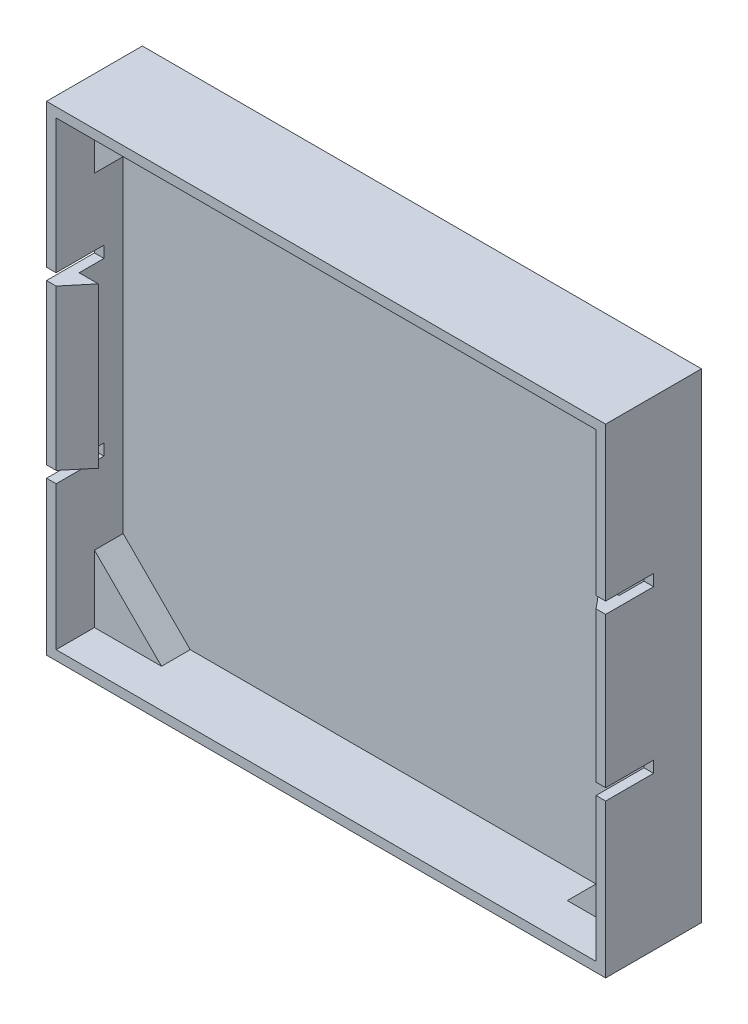
SolidWorks part; units mm, degrees
ref_plane "前基準面" through (0, 0, 0) normal (0, 0, 1) x (1, 0, 0)
ref_plane "上基準面" through (0, 0, 0) normal (0, 1, 0) x (1, 0, 0)
ref_plane "右基準面" through (0, 0, 0) normal (1, 0, 0) x (0, 0, -1)
sketch "草圖1" plane through (0, 0, 0) normal (0, 0, 1) x (1, 0, 0)
  line L1 (-24.8424, 31.8654) -> (33.5176, 31.8654)
  line L2 (-24.8424, 31.8654) -> (-24.8424, -18.2046)
  line L3 (-24.8424, -18.2046) -> (33.5176, -18.2046)
  line L4 (33.5176, 31.8654) -> (33.5176, -18.2046)
  dimension "D1" = 58.36
  dimension "D2" = 50.07
extrude "填料-伸長1" add sketch "草圖1" along normal blind 3
sketch "草圖2" plane through (0, 0, 3) normal (0, 0, 1) x (1, 0, 0)
  line L1 (-24.8424, 31.8654) -> (33.5176, 31.8654)
  line L2 (-24.8424, 31.8654) -> (-24.8424, -18.2046)
  line L3 (-24.8424, -18.2046) -> (33.5176, -18.2046)
  line L4 (33.5176, 31.8654) -> (33.5176, -18.2046)
  line L5 (-23.8424, 30.8654) -> (32.5176, 30.8654)
  line L6 (-23.8424, 30.8654) -> (-23.8424, -17.2046)
  line L7 (-23.8424, -17.2046) -> (32.5176, -17.2046)
  line L8 (32.5176, 30.8654) -> (32.5176, -17.2046)
  dimension "D1" = 1
  dimension "D2" = 1
  dimension "D3" = 1
  dimension "D4" = 1
extrude "填料-伸長2" add sketch "草圖2" along normal blind 7
sketch "草圖3" plane through (0, 0, 3) normal (0, 0, 1) x (1, 0, 0)
  line L0 (-23.8424, 30.8654) -> (-23.8424, 23.8654)
  line L1 (-23.8424, 30.8654) -> (-23.8424, -17.2046) construction
  line L2 (-23.8424, 23.8654) -> (-16.8424, 30.8654)
  line L3 (32.5176, 30.8654) -> (-23.8424, 30.8654) construction
  line L4 (-16.8424, 30.8654) -> (-23.8424, 30.8654)
  line L5 (32.5176, -17.2046) -> (32.5176, -10.2046)
  line L6 (32.5176, -17.2046) -> (32.5176, 30.8654) construction
  line L7 (32.5176, -10.2046) -> (25.5176, -17.2046)
  line L8 (-23.8424, -17.2046) -> (32.5176, -17.2046) construction
  line L9 (25.5176, -17.2046) -> (32.5176, -17.2046)
  line L10 (32.5176, 30.8654) -> (32.5176, 23.8654)
  line L11 (32.5176, 23.8654) -> (25.5176, 30.8654)
  line L12 (25.5176, 30.8654) -> (32.5176, 30.8654)
  line L13 (-23.8424, -17.2046) -> (-23.8424, -10.2046)
  line L14 (-23.8424, -10.2046) -> (-16.8424, -17.2046)
  line L15 (-16.8424, -17.2046) -> (-23.8424, -17.2046)
  dimension "D1" = 7
  dimension "D2" = 7
  dimension "D3" = 7
  dimension "D4" = 7
  dimension "D5" = 7
  dimension "D6" = 7
  dimension "D7" = 7
  dimension "D8" = 7
extrude "填料-伸長3" add sketch "草圖3" along normal blind 3
sketch "草圖4" plane through (0, 0, 10) normal (0, 0, 1) x (1, 0, 0)
  line L0 (33.5176, -18.2046) -> (33.5176, 31.8654) construction
  line L1 (33.5176, 15.8654) -> (32.5176, 15.8654)
  line L2 (33.5176, 15.8654) -> (33.5176, -2.2046)
  line L3 (33.5176, -2.2046) -> (32.5176, -2.2046)
  line L4 (32.5176, 15.8654) -> (32.5176, -2.2046)
  line L5 (32.5176, -17.2046) -> (32.5176, 30.8654) construction
  line L6 (-23.8424, -17.2046) -> (32.5176, -17.2046) construction
  line L7 (33.5176, 14.6654) -> (32.5176, 14.6654)
  line L8 (33.5176, 14.6654) -> (33.5176, -1.0046)
  line L9 (33.5176, -1.0046) -> (32.5176, -1.0046)
  line L10 (32.5176, 14.6654) -> (32.5176, -1.0046)
  line L11 (32.5176, 30.8654) -> (-23.8424, 30.8654) construction
  line L12 (-23.8424, 30.8654) -> (-23.8424, -17.2046) construction
  line L13 (-23.8424, 16.8654) -> (-24.8424, 16.8654)
  line L14 (-23.8424, 16.8654) -> (-23.8424, -2.2046)
  line L15 (-23.8424, -2.2046) -> (-24.8424, -2.2046)
  line L16 (-24.8424, 16.8654) -> (-24.8424, -2.2046)
  line L17 (-24.8424, 31.8654) -> (-24.8424, -18.2046) construction
  line L18 (33.5176, 31.8654) -> (-24.8424, 31.8654) construction
  line L19 (-23.8424, 15.6654) -> (-24.8424, 15.6654)
  line L20 (-23.8424, 15.6654) -> (-23.8424, -1.0046)
  line L21 (-23.8424, -1.0046) -> (-24.8424, -1.0046)
  line L22 (-24.8424, 15.6654) -> (-24.8424, -1.0046)
  point P28 (-24.3424, -2.2046)
  line M9 (-24.8424, 31.8654) -> (-24.8424, -18.2046)
  line M11 (33.5176, -18.2046) -> (33.5176, 31.8654)
  line M14 (-23.8424, -17.2046) -> (-23.8424, 30.8654)
  line M16 (32.5176, 30.8654) -> (32.5176, -17.2046)
  dimension "D1" = 15
  dimension "D2" = 1.2
  dimension "D3" = 1.2
  dimension "D4" = 15
  dimension "D5" = 1.2
  dimension "D6" = 1.2
  dimension "D7" = 15
  dimension "D8" = 15
extrude "除料-伸長1" cut sketch "草圖4" against normal blind 5 contours L21 L15 M14 M9 | L19 L14 L13 M9 | L9 L3 M11 M16 | L7 L2 L1 M16
sketch "草圖5" plane through (0, -1.0046, 0) normal (0, -1, 0) x (1, 0, 0)
  line L0 (32.5176, 10) -> (30.5176, 7.6)
  line L1 (30.5176, 7.6) -> (32.5176, 7.6)
  line L2 (32.5176, 5) -> (32.5176, 10) construction
  line L3 (32.5176, 7.6) -> (32.5176, 10)
  dimension "D1" = 2.4
  dimension "D2" = 2
extrude "填料-伸長4" add sketch "草圖5" against normal up to surface (15.67 mm away) up to face at (33.0176, 14.6654, 7.5)
sketch "草圖6" plane through (0, -1.0046, 0) normal (0, -1, 0) x (1, 0, 0)
  line L0 (-23.8424, 10) -> (-21.8424, 7.6)
  line L1 (-21.8424, 7.6) -> (-23.8424, 7.6)
  line L2 (-23.8424, 5) -> (-23.8424, 10) construction
  line L3 (-23.8424, 7.6) -> (-23.8424, 10)
  dimension "D1" = 2.4
  dimension "D2" = 90
  dimension "D3" = 2
extrude "填料-伸長5" add sketch "草圖6" against normal up to surface (16.67 mm away) up to face at (-24.3424, 15.6654, 7.5)
